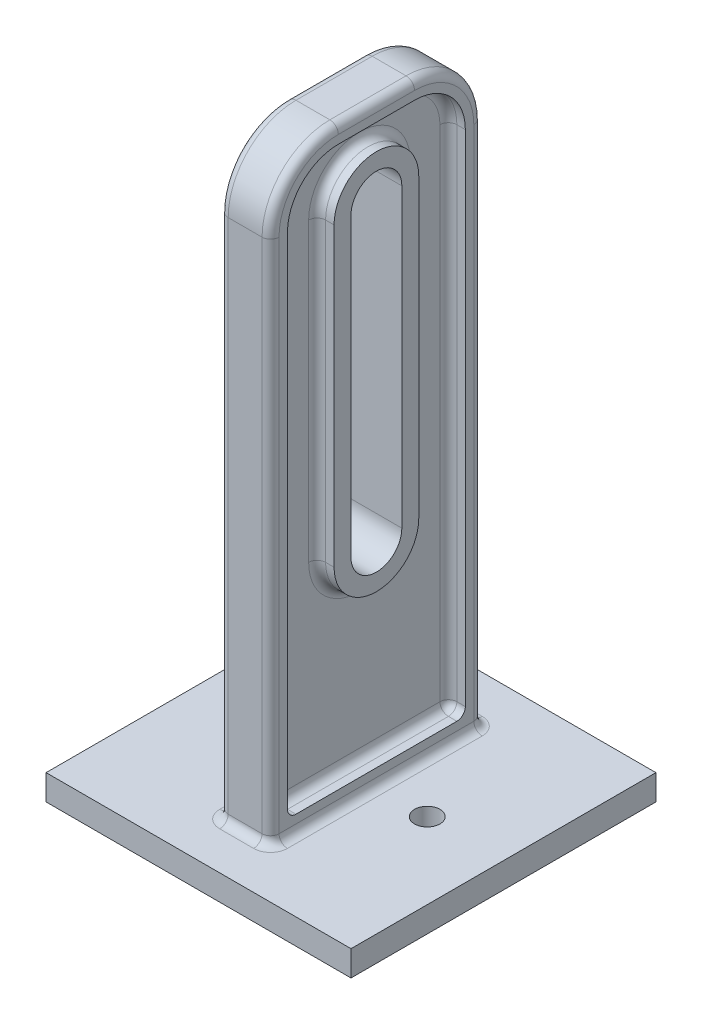
SolidWorks part; units mm, degrees
ref_plane "Front Plane" through (0, 0, 0) normal (0, 0, 1) x (1, 0, 0)
ref_plane "Top Plane" through (0, 0, 0) normal (0, 1, 0) x (1, 0, 0)
ref_plane "Right Plane" through (0, 0, 0) normal (1, 0, 0) x (0, 0, -1)
sketch "Sketch1" plane through (0, 0, 0) normal (0, 1, 0) x (1, 0, 0)
  line L1 (-18, -18) -> (18, -18)
  line L2 (-18, -18) -> (-18, 18)
  line L3 (-18, 18) -> (18, 18)
  line L4 (18, -18) -> (18, 18)
  line L5 (-18, -18) -> (18, 18) construction
  line L6 (-18, 18) -> (18, -18) construction
  point P0 (0, 0)
  dimension "D1" = 36
  dimension "D2" = 36
extrude "Boss-Extrude1" add sketch "Sketch1" along normal blind 3
sketch "Sketch2" plane through (0, 3, 0) normal (0, 1, 0) x (1, 0, 0)
  line L1 (-18, 0) -> (18, 0) construction
  line L2 (-18, 18) -> (-18, -18) construction
  line L3 (18, -18) -> (18, 18) construction
  circle A0 centre (-9, 0) radius 1.5
  circle A1 centre (9, 0) radius 1.5
  point P4 (0, 0)
  dimension "D1" = 3
  dimension "D2" = 9
  dimension "D3" = 9
extrude "Cut-Extrude1" cut sketch "Sketch2" against normal blind 3
sketch "Sketch3" plane through (0, 3, 0) normal (0, 1, 0) x (1, 0, 0)
  line L1 (-3, -12.5) -> (3, -12.5)
  line L2 (-3, -12.5) -> (-3, 12.5)
  line L3 (-3, 12.5) -> (3, 12.5)
  line L4 (3, -12.5) -> (3, 12.5)
  line L5 (-3, -12.5) -> (3, 12.5) construction
  line L6 (-3, 12.5) -> (3, -12.5) construction
  point P0 (0, 0)
  dimension "D1" = 25
  dimension "D2" = 6
extrude "Boss-Extrude2" add sketch "Sketch3" along normal blind 70
fillet "Fillet1" radius 8 2 edges at (0, 73, -12.5) (0, 73, 12.5)
sketch "Sketch5" plane through (3, 0, 0) normal (1, 0, 0) x (0, 0, -1)
  line L0 (0, 0) -> (0, 73) construction
  line L1 (-4.5, 73) -> (4.5, 73) construction
  line L2 (0, 63) -> (0, 28) construction
  line L3 (3, 63) -> (3, 28)
  line L4 (-3, 63) -> (-3, 28)
  arc A0 (3, 63) -> (-3, 63) centre (0, 63) ccw
  arc A1 (-3, 28) -> (3, 28) centre (0, 28) ccw
  point P7 (0, 45.5)
  point P12 (0, 17.4733)
  point P13 (0, 35.3354)
  point P14 (-13.8347, 64.2935)
  dimension "D1" = 3
  dimension "D3" = 35
  dimension "D2" = 10
extrude "Cut-Extrude3" cut sketch "Sketch5" against normal blind 6
sketch "Sketch6" plane through (3, 0, 0) normal (1, 0, 0) x (0, 0, -1)
  line L8 (10.5, 5) -> (10.5, 65)
  line L9 (4.5, 71) -> (-4.5, 71)
  line L10 (-10.5, 65) -> (-10.5, 5)
  line L11 (-10.5, 5) -> (10.5, 5)
  line L12 (10.5, 5) -> (10.5, 65)
  line L13 (4.5, 71) -> (-4.5, 71)
  line L14 (-10.5, 65) -> (-10.5, 5)
  line L15 (-10.5, 5) -> (10.5, 5)
  line L22 (-12.5, 65) -> (-12.5, 3) construction
  line L23 (12.5, 3) -> (-12.5, 3) construction
  line L24 (5, 28) -> (5, 63)
  line L25 (-5, 63) -> (-5, 28)
  line L26 (5, 28) -> (5, 63)
  line L27 (-5, 63) -> (-5, 28)
  line L28 (-12.5, 65) -> (-12.5, 3) construction
  arc A4 (10.5, 65) -> (4.5, 71) centre (4.5, 65) ccw
  arc A5 (-4.5, 71) -> (-10.5, 65) centre (-4.5, 65) ccw
  arc A6 (10.5, 65) -> (4.5, 71) centre (4.5, 65) ccw
  arc A7 (-4.5, 71) -> (-10.5, 65) centre (-4.5, 65) ccw
  arc A14 (-5, 28) -> (5, 28) centre (0, 28) ccw
  arc A15 (5, 63) -> (-5, 63) centre (0, 63) ccw
  arc A16 (-5, 28) -> (5, 28) centre (0, 28) ccw
  arc A17 (5, 63) -> (-5, 63) centre (0, 63) ccw
  dimension "D1" = 2
  dimension "D2" = 2
extrude "Cut-Extrude4" cut sketch "Sketch6" against normal blind 2
mirror "Mirror1" about plane through (0, 0, 0) normal (1, 0, 0) of "Cut-Extrude4"
fillet "Fillet2" radius 1 38 edges at (1, 45.5, -5) (1, 23, 0) (1, 45.5, 5) (-3, 34, -12.5) (-3, 70.6569, -10.1569) (-3, 73, 0) (-3, 70.6569, 10.1569) (3, 34, -12.5) (3, 70.6569, -10.1569) (3, 73, 0) (3, 70.6569, 10.1569) (1, 68, 0) (-3, 34, 12.5) (3, 34, 12.5) (0, 3, 12.5) (-3, 3, 0) (0, 3, -12.5) (3, 3, 0) (1, 35, -10.5) (1, 69.2426, -8.7426) (1, 71, 0) (1, 69.2426, 8.7426) (-1, 35, 10.5) (-1, 69.2426, 8.7426) (-1, 71, 0) (-1, 69.2426, -8.7426) (1, 35, 10.5) (-1, 35, -10.5) (-1, 5, 0) (1, 5, 0) (2, 5, 10.5) (-2, 5, 10.5) (-2, 5, -10.5) (2, 5, -10.5) (-1, 68, 0) (-1, 45.5, -5) (-1, 23, 0) (-1, 45.5, 5)
